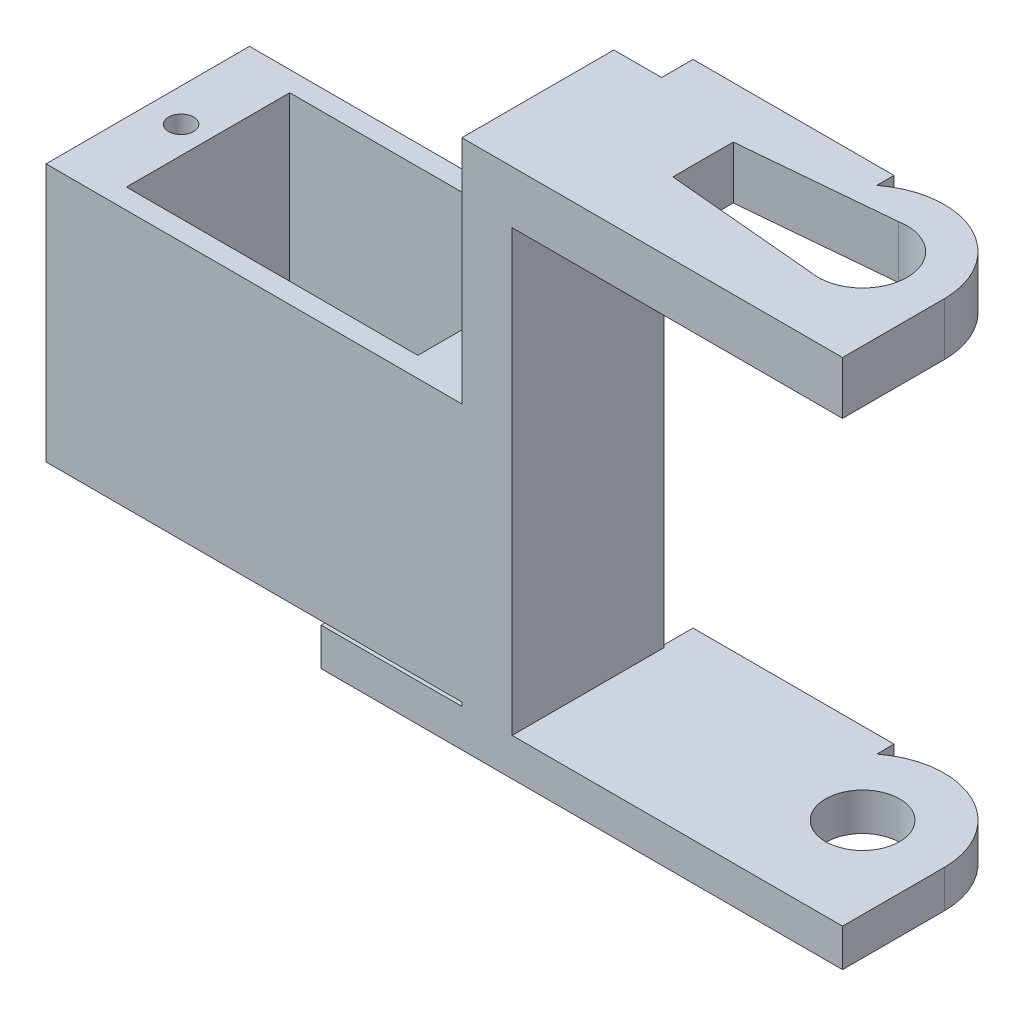
SolidWorks part; units mm, degrees
material "ABS"
ref_plane "Front Plane" through (0, 0, 0) normal (0, 0, 1) x (1, 0, 0)
ref_plane "Top Plane" through (0, 0, 0) normal (0, 1, 0) x (1, 0, 0)
ref_plane "Right Plane" through (0, 0, 0) normal (1, 0, 0) x (0, 0, -1)
sketch "Sketch1" plane through (0, 0, 0) normal (0, 1, 0) x (1, 0, 0)
  line L1 (35.1, -8.1) -> (67.9, -8.1)
  line L2 (35.1, -8.1) -> (35.1, 8.1)
  line L3 (35.1, 8.1) -> (67.9, 8.1)
  line L4 (67.9, -8.1) -> (67.9, 8.1)
extrude "Boss-Extrude1" add sketch "Sketch1" along normal mid plane 20.55 from offset 17.075
sketch "Sketch2" plane through (0, 0, 0) normal (0, 1, 0) x (1, 0, 0)
  line L0 (35.1, -8.1) -> (67.9, -8.1) construction
  line L1 (57, -8.1) -> (88, -8.1)
  line L2 (57, -8.1) -> (57, 4)
  line L3 (57, 4) -> (88, 4)
  line L4 (88, -8.1) -> (88, 4)
extrude "Boss-Extrude2" add sketch "Sketch2" along normal mid plane 3 from offset 5
sketch "Sketch3" plane through (0, 0, 0) normal (0, 1, 0) x (1, 0, 0)
  line L0 (57, -8.1) -> (88, -8.1) construction
  line L1 (72, -8.1) -> (88, -8.1)
  line L2 (72, -8.1) -> (72, 6.5)
  line L3 (72, 6.5) -> (88, 6.5)
  line L4 (88, -8.1) -> (88, 6.5)
extrude "Boss-Extrude3" add sketch "Sketch3" along normal mid plane 3 from offset 5
sketch "Sketch4" plane through (0, 0, 0) normal (0, 1, 0) x (1, 0, 0)
  line L1 (88, -8.1) -> (98.5, -8.1)
  line L2 (88, -8.1) -> (88, 0)
  line L3 (88, 0) -> (98.5, 0)
  line L4 (98.5, -8.1) -> (98.5, 0)
extrude "Boss-Extrude4" add sketch "Sketch4" along normal mid plane 3 from offset 5
sketch "Sketch5" plane through (0, 0, 0) normal (0, 1, 0) x (1, 0, 0)
  circle A0 centre (92, 0) radius 6.5
extrude "Boss-Extrude5" add sketch "Sketch5" along normal mid plane 3 from offset 5
sketch "Sketch6" plane through (0, 0, 0) normal (0, 1, 0) x (1, 0, 0)
  circle A0 centre (92, 0) radius 2.95
extrude "Cut-Extrude1" cut sketch "Sketch6" against normal mid plane 3 from offset 5
sketch "Sketch7" plane through (0, 0, 0) normal (1, 0, 0) x (0, 0, -1)
  line L1 (-8.1, 3.5) -> (4, 3.5)
  line L2 (-8.1, 3.5) -> (-8.1, 45.7)
  line L3 (-8.1, 45.7) -> (4, 45.7)
  line L4 (4, 3.5) -> (4, 45.7)
extrude "Boss-Extrude6" add sketch "Sketch7" along normal mid plane 4 from offset 70.2
sketch "Sketch8" plane through (0, 0, 0) normal (1, 0, 0) x (0, 0, -1)
  line L0 (4, 6.5) -> (4, 45.7) construction
  line L1 (-8.1, 6.8) -> (4, 6.8)
  line L2 (-8.1, 6.8) -> (-8.1, 27.35)
  line L3 (-8.1, 27.35) -> (4, 27.35)
  line L4 (4, 6.8) -> (4, 27.35)
extrude "Boss-Extrude7" add sketch "Sketch8" along normal mid plane 2.3 from offset 68.05
sketch "Sketch9" plane through (0, 0, 0) normal (0, 1, 0) x (1, 0, 0)
  line L1 (68.2, -8.1) -> (88, -8.1)
  line L2 (68.2, -8.1) -> (68.2, 4)
  line L3 (68.2, 4) -> (88, 4)
  line L4 (88, -8.1) -> (88, 4)
extrude "Boss-Extrude8" add sketch "Sketch9" along normal mid plane 4.2 from offset 43.6
sketch "Sketch10" plane through (0, 0, 0) normal (0, 1, 0) x (1, 0, 0)
  line L0 (88, -8.1) -> (68.2, -8.1) construction
  line L1 (72, -8.1) -> (88, -8.1)
  line L2 (72, -8.1) -> (72, 6.5)
  line L3 (72, 6.5) -> (88, 6.5)
  line L4 (88, -8.1) -> (88, 6.5)
extrude "Boss-Extrude9" add sketch "Sketch10" along normal mid plane 4.2 from offset 43.6
sketch "Sketch11" plane through (0, 0, 0) normal (0, 1, 0) x (1, 0, 0)
  line L1 (88, -8.1) -> (98.5, -8.1)
  line L2 (88, -8.1) -> (88, 0)
  line L3 (88, 0) -> (98.5, 0)
  line L4 (98.5, -8.1) -> (98.5, 0)
extrude "Boss-Extrude10" add sketch "Sketch11" along normal mid plane 4.2 from offset 43.6
sketch "Sketch12" plane through (0, 0, 0) normal (0, 1, 0) x (1, 0, 0)
  circle A0 centre (92, 0) radius 6.5
extrude "Boss-Extrude11" add sketch "Sketch12" along normal mid plane 4.2 from offset 43.6
sketch "Sketch13" plane through (0, 0, 0) normal (0, 1, 0) x (1, 0, 0)
  circle A0 centre (92, 0) radius 3.55
extrude "Cut-Extrude2" cut sketch "Sketch13" against normal mid plane 4.2 from offset 43.6
sketch "Sketch14" plane through (0, 0, 0) normal (0, 1, 0) x (1, 0, 0)
  line L0 (92, 3.55) -> (79.3, 2.4033)
  line L1 (79.3, 2.4033) -> (79.3, -2.4033)
  line L2 (79.3, -2.4033) -> (92, -3.55)
  line L3 (92, -3.55) -> (92, 3.55)
  circle A0 centre (92, 0) radius 3.55 construction
extrude "Cut-Extrude3" cut sketch "Sketch14" against normal mid plane 4.2 from offset 43.6
sketch "Sketch15" plane through (0, 0, 0) normal (0, 1, 0) x (1, 0, 0)
  line L1 (39.9, -6.5) -> (63.1, -6.5)
  line L2 (39.9, -6.5) -> (39.9, 6.5)
  line L3 (39.9, 6.5) -> (63.1, 6.5)
  line L4 (63.1, -6.5) -> (63.1, 6.5)
extrude "Cut-Extrude4" cut sketch "Sketch15" against normal mid plane 17.25 from offset 18.725
sketch "Sketch16" plane through (0, 0, 0) normal (0, 1, 0) x (1, 0, 0)
  circle A0 centre (65.25, 0) radius 1
extrude "Cut-Extrude5" cut sketch "Sketch16" against normal mid plane 6 from offset 24.35
sketch "Sketch17" plane through (0, 0, 0) normal (0, 1, 0) x (1, 0, 0)
  circle A0 centre (37.75, 0) radius 1
extrude "Cut-Extrude6" cut sketch "Sketch17" against normal mid plane 6 from offset 24.35
sketch "Sketch18" plane through (0, 0, 0) normal (0, 1, 0) x (1, 0, 0)
  circle A0 centre (46, 0) radius 3.15
extrude "Cut-Extrude7" cut sketch "Sketch18" against normal mid plane 2.6 from offset 8.1
sketch "Sketch19" plane through (0, 0, 0) normal (1, 0, 0) x (0, 0, -1)
  line L1 (-2.2, 10.1) -> (2.2, 10.1)
  line L2 (-2.2, 10.1) -> (-2.2, 16.1)
  line L3 (-2.2, 16.1) -> (2.2, 16.1)
  line L4 (2.2, 10.1) -> (2.2, 16.1)
extrude "Cut-Extrude8" cut sketch "Sketch19" against normal mid plane 4.8 from offset 37.5
